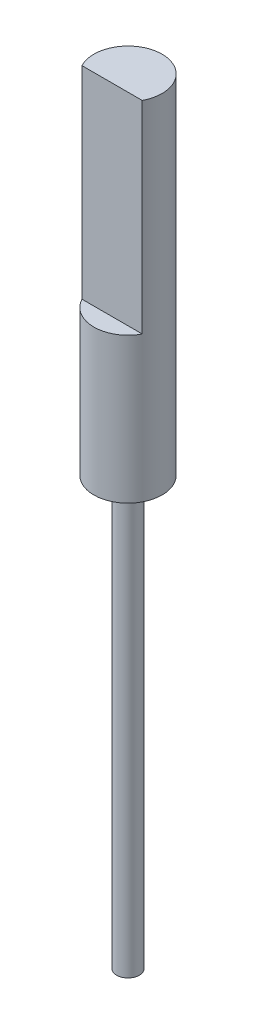
SolidWorks part; units mm, degrees
material "A286 Súper aleación a base de hierro"
ref_plane "Alzado" through (0, 0, 0) normal (0, 0, 1) x (1, 0, 0)
ref_plane "Planta" through (0, 0, 0) normal (0, 1, 0) x (1, 0, 0)
ref_plane "Vista lateral" through (0, 0, 0) normal (1, 0, 0) x (0, 0, -1)
sketch "Croquis1" plane through (0, 0, 0) normal (0, 1, 0) x (1, 0, 0)
  circle A0 centre (0, 0) radius 0.5
  dimension "D1" = 1
extrude "Saliente-Extruir1" add sketch "Croquis1" along normal blind 18.8
sketch "Croquis2" plane through (0, 18.8, 0) normal (0, 1, 0) x (1, 0, 0)
  circle A0 centre (0, 0) radius 1.5
  dimension "D1" = 3
extrude "Saliente-Extruir2" add sketch "Croquis2" along normal blind 15.3
sketch "Croquis3" plane through (0, 34.1, 0) normal (0, 1, 0) x (1, 0, 0)
  line L3 (-1.3266, -0.7) -> (1.3266, -0.7)
  circle A0 centre (0, 0) radius 1.5 construction
  arc A3 (-1.3266, -0.7) -> (1.3266, -0.7) centre (0, 0) ccw
  dimension "D1" = 0.7
extrude "Cortar-Extruir1" cut sketch "Croquis3" against normal blind 8.9
